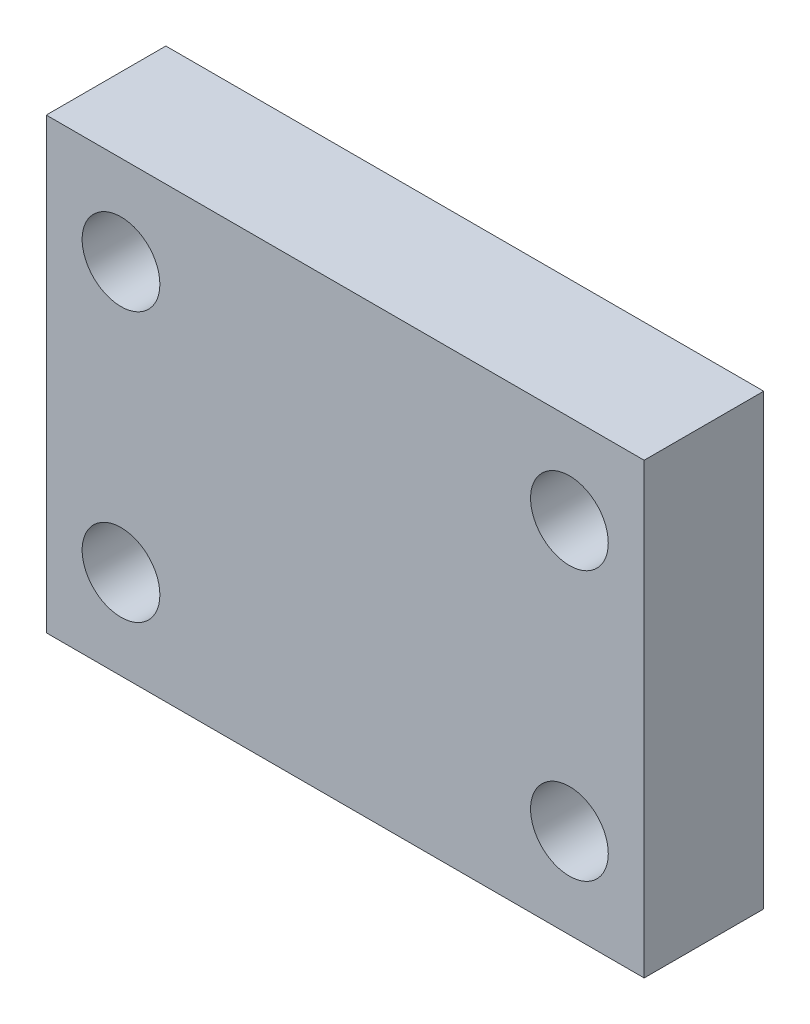
SolidWorks part; units mm, degrees
ref_plane "前视基准面" through (0, 0, 0) normal (0, 0, 1) x (1, 0, 0)
ref_plane "上视基准面" through (0, 0, 0) normal (0, 1, 0) x (1, 0, 0)
ref_plane "右视基准面" through (0, 0, 0) normal (1, 0, 0) x (0, 0, -1)
other "Configuration Table"
sketch "草图1" plane through (0, 0, 0) normal (0, 0, 1) x (1, 0, 0)
  line L1 (20, -15) -> (-20, -15)
  line L2 (20, -15) -> (20, 15)
  line L3 (20, 15) -> (-20, 15)
  line L4 (-20, -15) -> (-20, 15)
  line L5 (20, -15) -> (-20, 15) construction
  line L6 (20, 15) -> (-20, -15) construction
  circle A0 centre (-15, -9) radius 2.6
  circle A1 centre (15, -9) radius 2.6
  circle A2 centre (-15, 9) radius 2.6
  circle A3 centre (15, 9) radius 2.6
  point P0 (0, 0)
  dimension "D3" = 5.2
  dimension "D1" = 40
  dimension "D2" = 30
  dimension "D4" = 6
  dimension "D5" = 5
  dimension "D7" = 30
  dimension "D9" = 18
  dimension "D6" = 2
  dimension "D8" = 2
extrude "凸台-拉伸1" add sketch "草图1" along normal blind 8
